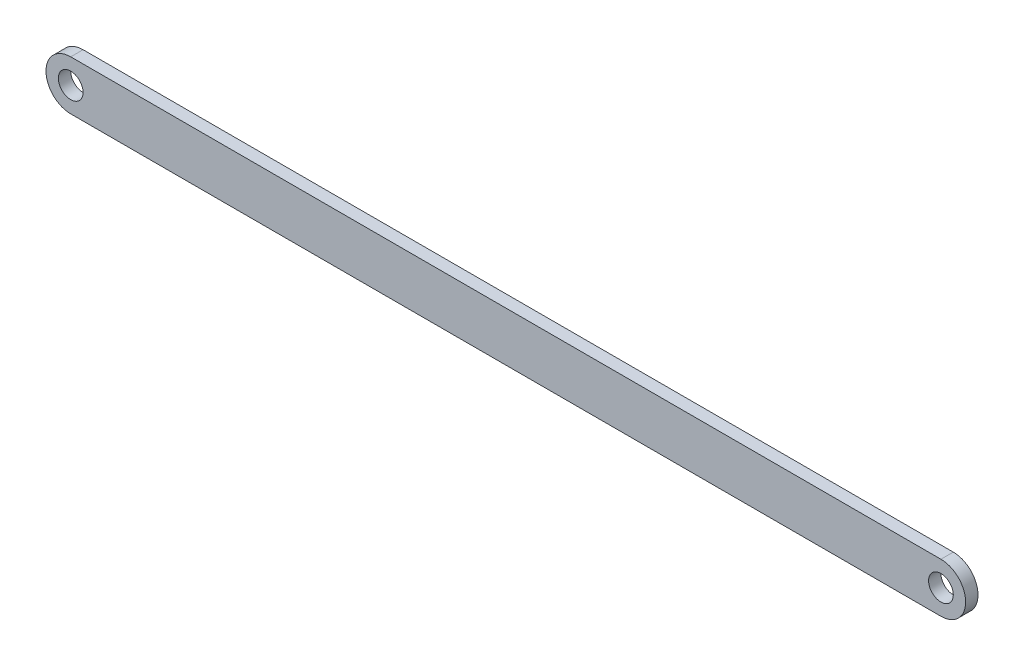
SolidWorks part; units mm, degrees
ref_plane "Plano frontal" through (0, 0, 0) normal (0, 0, 1) x (1, 0, 0)
ref_plane "Plano superior" through (0, 0, 0) normal (0, 1, 0) x (1, 0, 0)
ref_plane "Plano direito" through (0, 0, 0) normal (1, 0, 0) x (0, 0, -1)
sketch "Esboço1" plane through (0, 0, 0) normal (0, 0, 1) x (1, 0, 0)
  line L0 (-35.21, 2) -> (35.21, 2)
  line L1 (-35.21, 0) -> (35.21, 0) construction
  line L2 (-35.21, -2) -> (35.21, -2)
  arc A0 (-35.21, 2) -> (-35.21, -2) centre (-35.21, 0) ccw
  arc A1 (35.21, 2) -> (35.21, -2) centre (35.21, 0) cw
  circle A2 centre (-35.21, 0) radius 1
  circle A3 centre (35.21, 0) radius 1
  point P3 (0, 2)
  dimension "D1" = 70.42
  dimension "D2" = 2
extrude "Ressalto-extrusão1" add sketch "Esboço1" along normal blind 1
